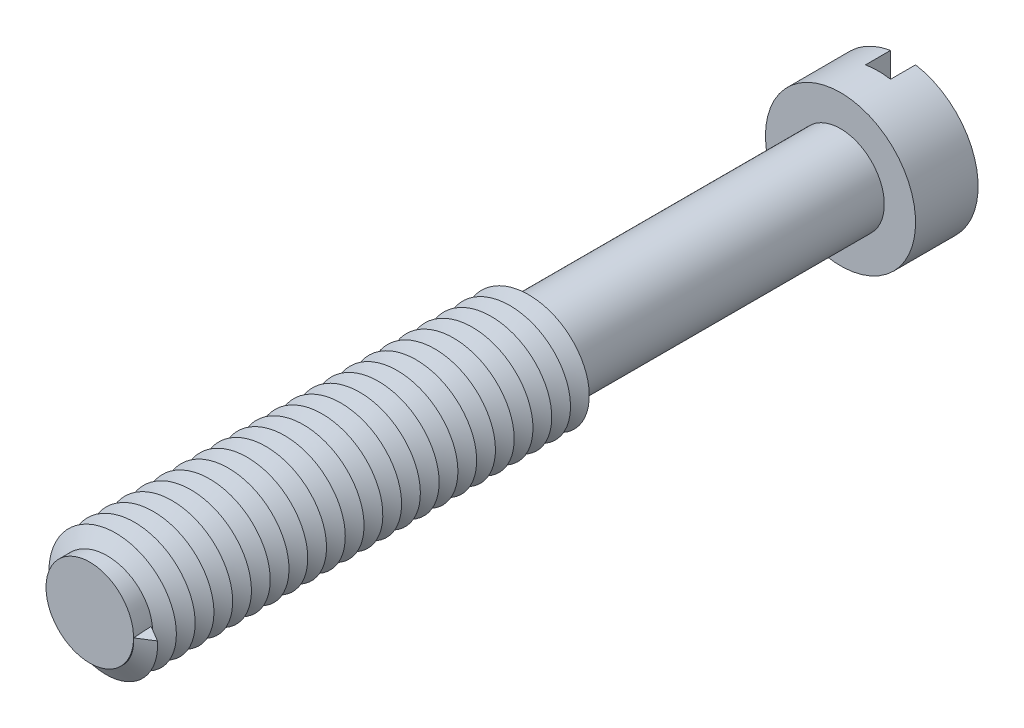
SolidWorks part; units mm, degrees
ref_plane "Front Plane" through (0, 0, 0) normal (0, 0, 1) x (1, 0, 0)
ref_plane "Top Plane" through (0, 0, 0) normal (0, 1, 0) x (1, 0, 0)
ref_plane "Right Plane" through (0, 0, 0) normal (1, 0, 0) x (0, 0, -1)
sketch "Sketch1" plane through (0, 0, 0) normal (0, 0, 1) x (1, 0, 0)
  circle A0 centre (0, 0) radius 3.5
  dimension "D1" = 7
extrude "Boss-Extrude1" add sketch "Sketch1" along normal blind 60
sketch "Sketch2" plane through (0, 0, 60) normal (0, 0, 1) x (1, 0, 0)
  circle A0 centre (0, 0) radius 3.5 construction
  circle A1 centre (0, 0) radius 3.5
curve "Helix/Spiral1" pitch 1.5 height 35 turns 23.3333
ref_plane "Plane1" through (3.5, 0, 60) normal (0, -0.9977, -0.0681) x (-1, 0, 0)
sketch "Sketch3" plane through (3.5, 0, 60) normal (0, -0.9977, -0.0681) x (-1, 0, 0)
  line L0 (0, 1.4) -> (0, 0)
  line L1 (0, 0) -> (-1.2124, 0.7)
  line L2 (-1.2124, 0.7) -> (0, 1.4)
  dimension "D1" = 1.4
sweep "Sweep1" add profiles "Sketch3" path "Helix/Spiral1"
sketch "Sketch4" plane through (0, 0, 0) normal (0, 0, -1) x (-1, 0, 0)
  circle A0 centre (0, 0) radius 6
  dimension "D1" = 12
extrude "Boss-Extrude2" add sketch "Sketch4" along normal blind 5
sketch "Sketch5" plane through (0, 0, -5) normal (0, 0, -1) x (-1, 0, 0)
  line L0 (0, 6) -> (0, -6) construction
  line L1 (-1, 6) -> (-1, -6)
  line L2 (1, 6) -> (1, -6)
  line L3 (-1, 6) -> (1, 6)
  line L4 (-1, -6) -> (1, -6)
  circle A0 centre (0, 0) radius 6 construction
  dimension "D1" = 1
  dimension "D2" = 1
extrude "Cut-Extrude1" cut sketch "Sketch5" against normal blind 2
